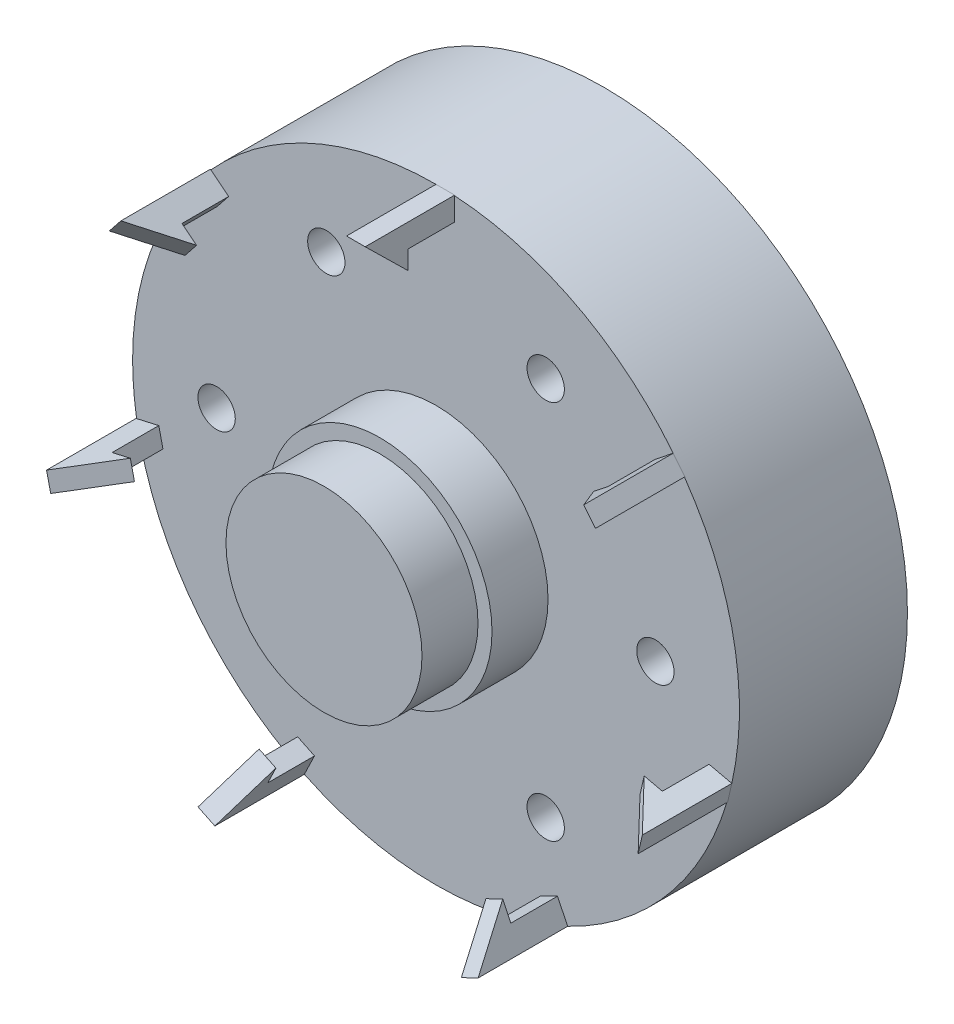
SolidWorks part; units mm, degrees
ref_plane "Front Plane" through (0, 0, 0) normal (0, 0, 1) x (1, 0, 0)
ref_plane "Top Plane" through (0, 0, 0) normal (0, 1, 0) x (1, 0, 0)
ref_plane "Right Plane" through (0, 0, 0) normal (1, 0, 0) x (0, 0, -1)
sketch "Sketch2" plane through (0, 0, 0) normal (0, 0, 1) x (1, 0, 0)
  circle A0 centre (0, 0) radius 32.5
  dimension "D1" = 65
extrude "Boss-Extrude1" add sketch "Sketch2" along normal blind 10
sketch "Sketch3" plane through (0, 0, 0) normal (1, 0, 0) x (0, 0, -1)
  line L0 (-10, 32.5) -> (-19.5879, 32.5)
  line L4 (-19.5879, 32.5) -> (-15, 28)
  line L5 (-15, 28) -> (-15, 30)
  line L6 (-15, 30) -> (-10, 30)
  line L7 (-10, 32.5) -> (-10, -32.5) construction
  line L8 (-10, 30) -> (-10, 32.5)
  dimension "D1" = 2.5
  dimension "D2" = 2
  dimension "D3" = 5
extrude "Boss-Extrude2" add sketch "Sketch3" along normal blind 2
pattern_circular "CirPattern1" count 7 over 360 about axis through (0, 0, 0) along (0, 0, 1) of "Boss-Extrude2"
sketch "Sketch4" plane through (0, 0, 10) normal (0, 0, 1) x (1, 0, 0)
  circle A0 centre (0, 0) radius 12
  dimension "D1" = 24
extrude "Boss-Extrude3" add sketch "Sketch4" along normal blind 6
sketch "Sketch5" plane through (0, 0, 10) normal (0, 0, 1) x (1, 0, 0)
  circle A0 centre (0, 0) radius 10.5
  dimension "D1" = 21
extrude "Boss-Extrude4" add sketch "Sketch5" along normal blind 12
sketch "Sketch7" plane through (0, 0, 0) normal (0, 0, -1) x (-1, 0, 0)
  circle A0 centre (0, 0) radius 32.5
extrude "Boss-Extrude5" add sketch "Sketch7" along normal blind 8
sketch "Sketch6" plane through (0, 0, 10) normal (0, 0, 1) x (1, 0, 0)
  circle A0 centre (0, 0) radius 23.5 construction
  circle A1 centre (23.5, 0) radius 2
  circle A2 centre (11.75, -20.3516) radius 2
  circle A3 centre (-11.75, -20.3516) radius 2
  circle A4 centre (-23.5, 0) radius 2
  circle A5 centre (-11.75, 20.3516) radius 2
  circle A6 centre (11.75, 20.3516) radius 2
  point P17 (0, 0)
  dimension "D1" = 47
  dimension "D2" = 4
  dimension "D3" = 6
extrude "Cut-Extrude1" cut sketch "Sketch6" against normal through all
